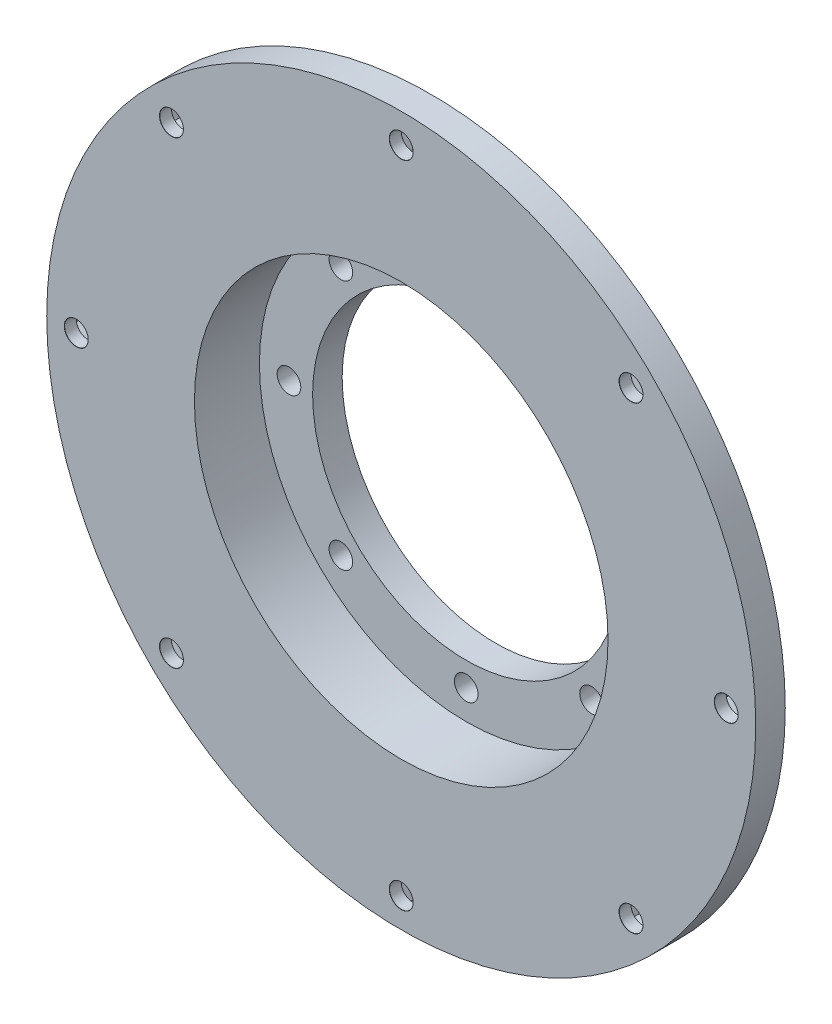
SolidWorks part; units mm, degrees
ref_plane "Front Plane" through (0, 0, 0) normal (0, 0, 1) x (1, 0, 0)
ref_plane "Top Plane" through (0, 0, 0) normal (0, 1, 0) x (1, 0, 0)
ref_plane "Right Plane" through (0, 0, 0) normal (1, 0, 0) x (0, 0, -1)
sketch "Sketch1" plane through (0, 0, 0) normal (0, 0, 1) x (1, 0, 0)
  line L0 (0, 0) -> (0, 63.1981) construction
  circle A0 centre (0, 0) radius 35
  circle A1 centre (0, 0) radius 26
  point P3 (0, 30)
  point P5 (21.2132, 21.2132)
  point P8 (30, 0)
  point P9 (21.2132, -21.2132)
  point P10 (0, -30)
  point P11 (-21.2132, -21.2132)
  point P12 (-30, 0)
  point P13 (-21.2132, 21.2132)
  point P14 (0, 0)
  dimension "D1" = 70
  dimension "D4" = 52
  dimension "D2" = 30
  dimension "D3" = 8
extrude "Boss-Extrude1" add sketch "Sketch1" along normal blind 5
sketch "Sketch2" plane through (0, 0, 0) normal (0, 0, 1) x (1, 0, 0)
  line L0 (0, 0) -> (0, 63.1981) construction
  circle A0 centre (0, 0) radius 45
  point P3 (0, 30)
  point P5 (21.2132, 21.2132)
  point P8 (30, 0)
  point P9 (21.2132, -21.2132)
  point P10 (0, -30)
  point P11 (-21.2132, -21.2132)
  point P12 (-30, 0)
  point P13 (-21.2132, 21.2132)
  point P14 (0, 0)
  dimension "D1" = 90
  dimension "D2" = 30
  dimension "D3" = 8
hole_wizard "Ø4.0mm Dowel Hole1" positions "Sketch3" profile "Sketch4" hole size "Ø4.0" standard "ISO" end condition through all
sketch "Sketch3" plane through (0, 0, 0) normal (0, 0, -1) x (-1, 0, 0)
  point P0 (21.2132, 21.2132)
  point P3 (0, 30)
  point P6 (-21.2132, 21.2132)
  point P9 (-30, 0)
  point P12 (-21.2132, -21.2132)
  point P15 (0, -30)
  point P18 (21.2132, -21.2132)
  point P21 (30, 0)
sketch "Sketch4" plane through (-21.2132, 21.2132, 0) normal (1, 0, 0) x (0, 1, 0)
  line L0 (0, 0) -> (0, 5)
  line L1 (0, 5) -> (2, 5)
  line L2 (2, 5) -> (2, 0.025)
  line L3 (2, 0.025) -> (2.025, 0)
  line L5 (2.025, 0) -> (0, 0)
  line L6 (-2, 0.025) -> (-2.025, 0) construction
  line L11 (0, -6.35) -> (0, 107.95) construction
  dimension "Thru Hole Dia." = 4
  dimension "Thru Hole Depth" = 5
  dimension "Near C'Sink Dia." = 4.05
  dimension "Near C'Sink Angle" = 90
ref_plane "Plane1" through (0, 0, 0) normal (0, 0, -1) x (-1, 0, 0)
sketch "Sketch5" plane through (0, 0, 0) normal (0, 0, -1) x (-1, 0, 0)
  circle A0 centre (0, 0) radius 40
  circle A1 centre (0, 0) radius 35
  dimension "D1" = 80
extrude "Boss-Extrude2" add sketch "Sketch5" against normal blind 16 contours A0 A1
ref_plane "Plane2" through (0, 0, 16) normal (0, 0, 1) x (1, 0, 0)
sketch "Sketch6" plane through (0, 0, 16) normal (0, 0, 1) x (1, 0, 0)
  circle A0 centre (0, 0) radius 60
  circle A1 centre (0, 0) radius 35
  dimension "D1" = 120
extrude "Boss-Extrude3" add sketch "Sketch6" against normal blind 5
sketch "Sketch7" plane through (0, 0, 16) normal (0, 0, 1) x (1, 0, 0)
  line L0 (0, 0) -> (0, 63.1981) construction
  circle A0 centre (0, 0) radius 45
  point P3 (0, 55)
  point P5 (38.8909, 38.8909)
  point P8 (55, 0)
  point P9 (38.8909, -38.8909)
  point P10 (0, -55)
  point P11 (-38.8909, -38.8909)
  point P12 (-55, 0)
  point P13 (-38.8909, 38.8909)
  point P14 (0, 0)
  dimension "D1" = 90
  dimension "D2" = 55
  dimension "D3" = 8
hole_wizard "Ø4.0mm Dowel Hole2" positions "Sketch8" profile "Sketch9" hole size "Ø4.0" standard "ISO" end condition through all
sketch "Sketch8" plane through (0, 0, 16) normal (0, 0, 1) x (1, 0, 0)
  point P0 (0, 55)
  point P3 (-38.8909, 38.8909)
  point P6 (-55, 0)
  point P9 (-38.8909, -38.8909)
  point P12 (0, -55)
  point P15 (38.8909, -38.8909)
  point P18 (55, 0)
  point P21 (38.8909, 38.8909)
sketch "Sketch9" plane through (0, 55, 16) normal (1, 0, 0) x (0, -1, 0)
  line L0 (0, 0) -> (0, 16)
  line L1 (0, 16) -> (2, 16)
  line L2 (2, 16) -> (2, 0.025)
  line L3 (2, 0.025) -> (2.025, 0)
  line L5 (2.025, 0) -> (0, 0)
  line L6 (-2, 0.025) -> (-2.025, 0) construction
  line L11 (0, -6.35) -> (0, 107.95) construction
  dimension "Thru Hole Dia." = 4
  dimension "Thru Hole Depth" = 16
  dimension "Near C'Sink Dia." = 4.05
  dimension "Near C'Sink Angle" = 90
ref_plane "Plane3" through (0, 0, 11) normal (0, 0, -1) x (-1, 0, 0)
sketch "Sketch11" plane through (0, 0, 11) normal (0, 0, -1) x (-1, 0, 0)
  line L0 (0, 0) -> (0, 63.1981) construction
  line L1 (41.9936, 35.7882) -> (43.1292, 40.0265)
  line L2 (4.3879, 55) -> (2.1939, 58.8)
  line L3 (2.1939, 58.8) -> (-2.1939, 58.8)
  line L4 (-2.1939, 58.8) -> (-4.3879, 55)
  line L5 (-4.3879, 55) -> (-2.1939, 51.2)
  line L6 (-2.1939, 51.2) -> (2.1939, 51.2)
  line L7 (2.1939, 51.2) -> (4.3879, 55)
  line L8 (43.1292, 40.0265) -> (40.0265, 43.1292)
  line L9 (40.0265, 43.1292) -> (35.7882, 41.9936)
  line L10 (35.7882, 41.9936) -> (34.6525, 37.7552)
  line L11 (34.6525, 37.7552) -> (37.7552, 34.6525)
  line L12 (37.7552, 34.6525) -> (41.9936, 35.7882)
  line L13 (55, -4.3879) -> (58.8, -2.1939)
  line L14 (58.8, -2.1939) -> (58.8, 2.1939)
  line L15 (58.8, 2.1939) -> (55, 4.3879)
  line L16 (55, 4.3879) -> (51.2, 2.1939)
  line L17 (51.2, 2.1939) -> (51.2, -2.1939)
  line L18 (51.2, -2.1939) -> (55, -4.3879)
  line L19 (35.7882, -41.9936) -> (40.0265, -43.1292)
  line L20 (40.0265, -43.1292) -> (43.1292, -40.0265)
  line L21 (43.1292, -40.0265) -> (41.9936, -35.7882)
  line L22 (41.9936, -35.7882) -> (37.7552, -34.6525)
  line L23 (37.7552, -34.6525) -> (34.6525, -37.7552)
  line L24 (34.6525, -37.7552) -> (35.7882, -41.9936)
  line L25 (-4.3879, -55) -> (-2.1939, -58.8)
  line L26 (-2.1939, -58.8) -> (2.1939, -58.8)
  line L27 (2.1939, -58.8) -> (4.3879, -55)
  line L28 (4.3879, -55) -> (2.1939, -51.2)
  line L29 (2.1939, -51.2) -> (-2.1939, -51.2)
  line L30 (-2.1939, -51.2) -> (-4.3879, -55)
  line L31 (-41.9936, -35.7882) -> (-43.1292, -40.0265)
  line L32 (-43.1292, -40.0265) -> (-40.0265, -43.1292)
  line L33 (-40.0265, -43.1292) -> (-35.7882, -41.9936)
  line L34 (-35.7882, -41.9936) -> (-34.6525, -37.7552)
  line L35 (-34.6525, -37.7552) -> (-37.7552, -34.6525)
  line L36 (-37.7552, -34.6525) -> (-41.9936, -35.7882)
  line L37 (-55, 4.3879) -> (-58.8, 2.1939)
  line L38 (-58.8, 2.1939) -> (-58.8, -2.1939)
  line L39 (-58.8, -2.1939) -> (-55, -4.3879)
  line L40 (-55, -4.3879) -> (-51.2, -2.1939)
  line L41 (-51.2, -2.1939) -> (-51.2, 2.1939)
  line L42 (-51.2, 2.1939) -> (-55, 4.3879)
  line L43 (-35.7882, 41.9936) -> (-40.0265, 43.1292)
  line L44 (-40.0265, 43.1292) -> (-43.1292, 40.0265)
  line L45 (-43.1292, 40.0265) -> (-41.9936, 35.7882)
  line L46 (-41.9936, 35.7882) -> (-37.7552, 34.6525)
  line L47 (-37.7552, 34.6525) -> (-34.6525, 37.7552)
  line L48 (-34.6525, 37.7552) -> (-35.7882, 41.9936)
  circle A0 centre (0, 0) radius 45
  circle A1 centre (0, 55) radius 3.8 construction
  point P3 (0, 55)
  point P5 (38.8909, 38.8909)
  point P8 (55, 0)
  point P9 (38.8909, -38.8909)
  point P10 (0, -55)
  point P11 (-38.8909, -38.8909)
  point P12 (-55, 0)
  point P13 (-38.8909, 38.8909)
  point P14 (0, 0)
  point P65 (0, 0)
  dimension "D1" = 90
  dimension "D4" = 8
  dimension "D2" = 55
  dimension "D3" = 8
extrude "Cut-Extrude3" cut sketch "Sketch11" against normal blind 3 contours L47 L48 L43 L44 L45 L46 | L6 L7 L2 L3 L4 L5 | L11 L12 L1 L8 L9 L10 | L41 L42 L37 L38 L39 L40 | L17 L18 L13 L14 L15 L16 | L23 L24 L19 L20 L21 L22 | L29 L30 L25 L26 L27 L28 | L35 L36 L31 L32 L33 L34
